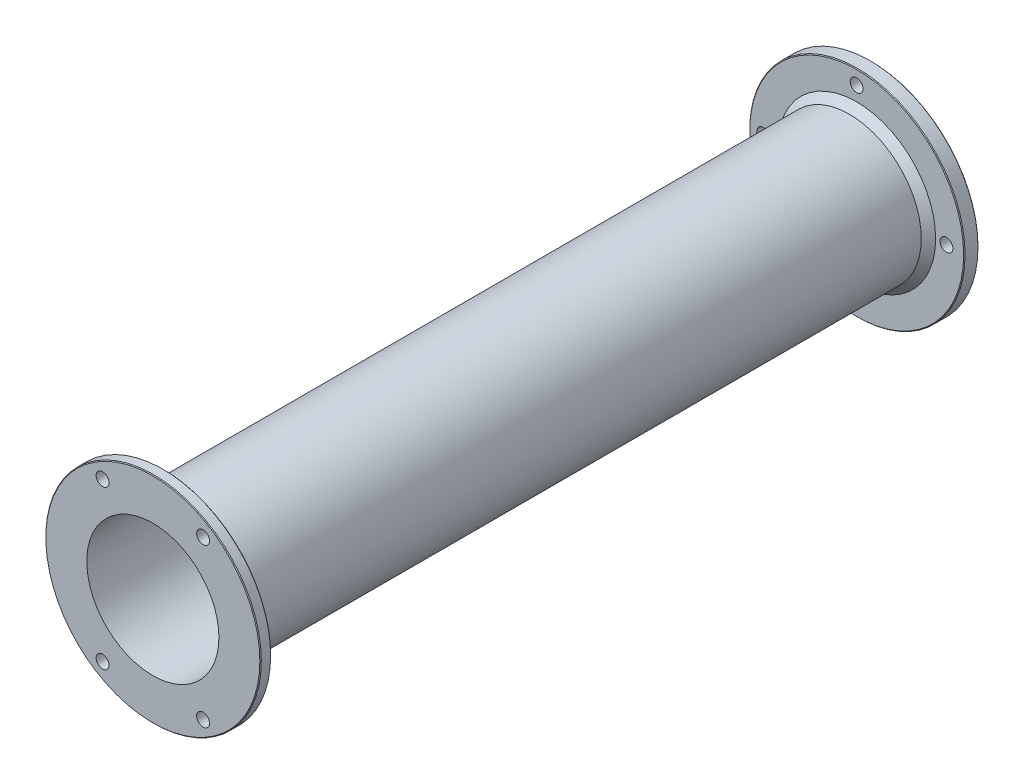
SolidWorks part; units mm, degrees
material "1.0045 (S355JR)"
ref_plane "Ebene vorne" through (0, 0, 0) normal (0, 0, 1) x (1, 0, 0)
ref_plane "Ebene oben" through (0, 0, 0) normal (0, 1, 0) x (1, 0, 0)
ref_plane "Ebene rechts" through (0, 0, 0) normal (1, 0, 0) x (0, 0, -1)
sketch "Skizze1" plane through (0, 0, 0) normal (0, 0, 1) x (1, 0, 0)
  line L0 (0, 0) -> (0, 130) construction
  circle A0 centre (0, 0) radius 150
  circle A1 centre (0, 0) radius 92
  circle A2 centre (0, 130) radius 9
  circle A3 centre (125, 0) radius 9
  circle A4 centre (-5, -125) radius 9
  circle A5 centre (-130, 5) radius 9
  point P15 (-2.5, 2.5)
  dimension "D1" = 300
  dimension "D2" = 18
  dimension "D5" = 184
  dimension "D3" = 130
  dimension "D4" = 4
extrude "Aufsatz-Linear austragen1" add sketch "Skizze1" along normal blind 20
sketch "Skizze2" plane through (0, 0, 20) normal (0, 0, 1) x (1, 0, 0)
  circle A0 centre (0, 0) radius 100
  circle A1 centre (0, 0) radius 92 construction
  circle A2 centre (0, 0) radius 92
  dimension "D1" = 200
extrude "Aufsatz-Linear austragen2" add sketch "Skizze2" along normal blind 965
sketch "Skizze3" plane through (0, 0, 985) normal (0, 0, 1) x (1, 0, 0)
  line L1 (70, -110) -> (-70, -110) construction
  line L2 (70, -110) -> (70, 110) construction
  line L3 (70, 110) -> (-70, 110) construction
  line L4 (-70, -110) -> (-70, 110) construction
  line L5 (70, -110) -> (-70, 110) construction
  line L6 (70, 110) -> (-70, -110) construction
  circle A0 centre (0, 0) radius 92 construction
  circle A1 centre (0, 0) radius 92
  circle A2 centre (-70, 110) radius 9
  circle A3 centre (70, 110) radius 9
  circle A4 centre (70, -110) radius 9
  circle A5 centre (-70, -110) radius 9
  circle A6 centre (0, 0) radius 150
  dimension "D3" = 18
  dimension "D4" = 300
  dimension "D1" = 140
  dimension "D2" = 220
extrude "Aufsatz-Linear austragen3" add sketch "Skizze3" along normal blind 15
chamfer "Fase1" distance 10 angle 45 2 edges at (100, 0, 985) (100, 0, 20)
chamfer "Fase2" distance 1 angle 45 4 edges at (150, 0, 0) (150, 0, 20) (150, 0, 985) (150, 0, 1000)
equation "\"D5@Skizze1\"=200-2*8"
